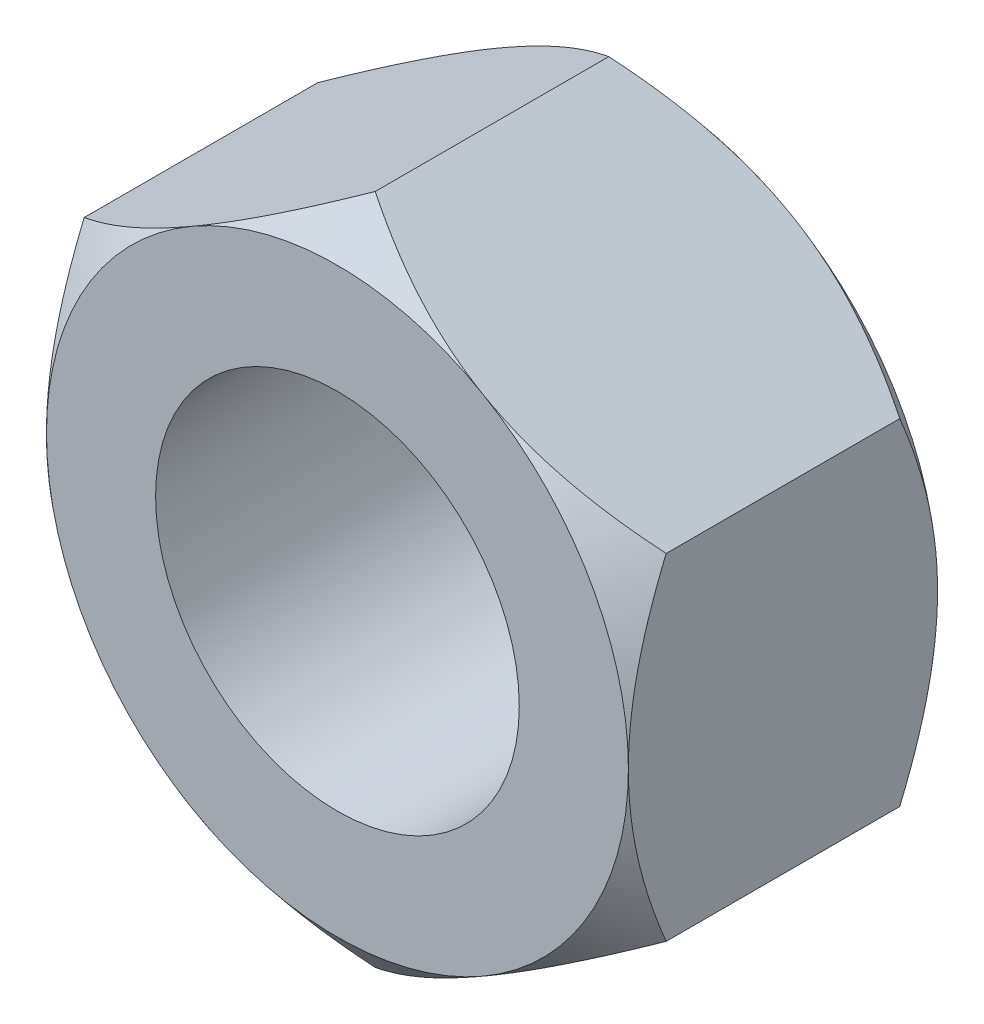
SolidWorks part; units mm, degrees
material "Alloy Steel"
ref_plane "Front Plane" through (0, 0, 0) normal (0, 0, 1) x (1, 0, 0)
ref_plane "Top Plane" through (0, 0, 0) normal (0, 1, 0) x (1, 0, 0)
ref_plane "Right Plane" through (0, 0, 0) normal (1, 0, 0) x (0, 0, -1)
sketch "Sketch1" plane through (0, 0, 0) normal (0, 0, 1) x (1, 0, 0)
  line L1 (0, 7.3323) -> (-6.35, 3.6662)
  line L2 (-6.35, 3.6662) -> (-6.35, -3.6662)
  line L3 (-6.35, -3.6662) -> (0, -7.3323)
  line L4 (0, -7.3323) -> (6.35, -3.6662)
  line L5 (6.35, -3.6662) -> (6.35, 3.6662)
  line L6 (6.35, 3.6662) -> (0, 7.3323)
  circle A0 centre (0, 0) radius 6.35 construction
  dimension "D1" = 12.7
extrude "Extrude1" add sketch "Sketch1" along normal blind 3.3734
sketch "Sketch2" plane through (0, 0, 3.3734) normal (0, 0, 1) x (1, 0, 0)
  circle A0 centre (0, 0) radius 3.9688
  dimension "D1" = 7.9375
extrude "Cut-Extrude1" cut sketch "Sketch2" against normal through all
sketch "Sketch3" plane through (0, 0, 0) normal (0, 1, 0) x (1, 0, 0)
  line L0 (6.35, -3.3734) -> (9.525, -0.7093)
  line L1 (9.525, -0.7093) -> (9.525, -3.3734)
  line L2 (9.525, -3.3734) -> (6.35, -3.3734)
  line L3 (6.35, -3.3734) -> (6.35, 0) construction
  dimension "D1" = 40
  dimension "D2" = 3.175
revolve "Cut-Revolve1" cut sketch "Sketch3" angle 360 about axis through (0, 0, 0) along (0, 0, 1)
mirror "Mirror1" about plane through (0, 7.3323, 0) normal (0, 0, 1) of "Cut-Extrude1", "Extrude1", "Cut-Revolve1"
